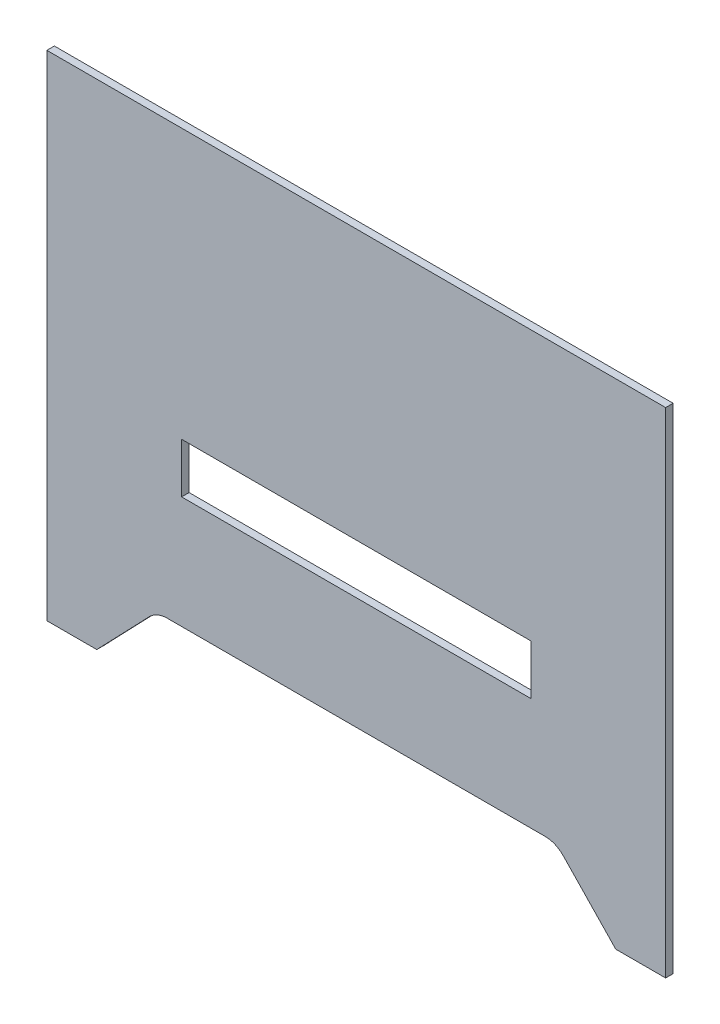
SolidWorks part; units mm, degrees
ref_plane "前视基准面" through (0, 0, 0) normal (0, 0, 1) x (1, 0, 0)
ref_plane "上视基准面" through (0, 0, 0) normal (0, 1, 0) x (1, 0, 0)
ref_plane "右视基准面" through (0, 0, 0) normal (1, 0, 0) x (0, 0, -1)
sketch "Sketch1" plane through (0, 0, 0) normal (0, 0, 1) x (1, 0, 0)
  line L0 (0, -99) -> (0, 0) construction
  line L1 (-124, -99) -> (124, -99) construction
  line L2 (-124, -99) -> (-124, 99)
  line L3 (-124, 99) -> (124, 99)
  line L4 (124, -99) -> (124, 99)
  line L5 (-124, -99) -> (124, 99) construction
  line L6 (-124, 99) -> (124, -99) construction
  line L7 (-75.7378, -74) -> (75.7378, -74)
  line L8 (82.9517, -77.0747) -> (104, -99)
  line L9 (104, -99) -> (124, -99)
  line L10 (-104, -99) -> (-124, -99)
  line L11 (-82.9517, -77.0747) -> (-104, -99)
  line L13 (-70, -29) -> (70, -29)
  line L14 (-70, -29) -> (-70, -9)
  line L15 (-70, -9) -> (70, -9)
  line L16 (70, -29) -> (70, -9)
  line L17 (-70, -29) -> (70, -9) construction
  line L18 (-70, -9) -> (70, -29) construction
  arc A0 (82.9517, -77.0747) -> (75.7378, -74) centre (75.7378, -84) ccw
  arc A1 (-82.9517, -77.0747) -> (-75.7378, -74) centre (-75.7378, -84) cw
  point P0 (0, 0)
  point P8 (0, -19)
  point P13 (80, -74)
  point P18 (0, -74)
  dimension "D6" = 10
  dimension "D1" = 248
  dimension "D2" = 198
  dimension "D3" = 25
  dimension "D4" = 20
  dimension "D5" = 80
  dimension "D7" = 140
  dimension "D8" = 20
  dimension "D9" = 108
extrude "Boss-Extrude1" add sketch "Sketch1" along normal blind 3
